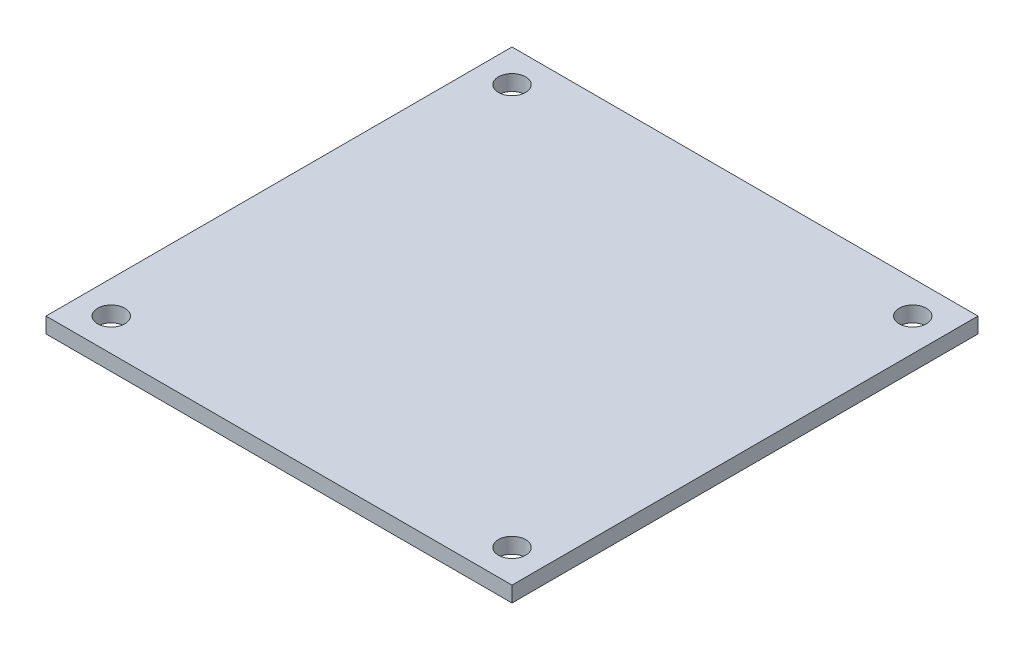
SolidWorks part; units mm, degrees
ref_plane "前视基准面" through (0, 0, 0) normal (0, 0, 1) x (1, 0, 0)
ref_plane "上视基准面" through (0, 0, 0) normal (0, 1, 0) x (1, 0, 0)
ref_plane "右视基准面" through (0, 0, 0) normal (1, 0, 0) x (0, 0, -1)
sketch "草图1" plane through (0, 0, 0) normal (0, 1, 0) x (1, 0, 0)
  line L1 (-30, -30) -> (30, -30)
  line L2 (-30, -30) -> (-30, 30)
  line L3 (-30, 30) -> (30, 30)
  line L4 (30, -30) -> (30, 30)
  line L5 (-30, -30) -> (30, 30) construction
  line L6 (-30, 30) -> (30, -30) construction
  point P0 (0, 0)
  dimension "D1" = 60
  dimension "D2" = 60
extrude "凸台-拉伸1" add sketch "草图1" along normal blind 2
sketch "草图2" plane through (0, 0, 0) normal (0, -1, 0) x (1, 0, 0)
  line L0 (-33.1976, 0) -> (33.3576, 0) construction
  line L1 (0, 32.0617) -> (0, -34.3655) construction
  circle A0 centre (-25.8, 25.8) radius 1.75
  circle A1 centre (25.8, 25.8) radius 1.75
  circle A2 centre (25.8, -25.8) radius 1.75
  circle A3 centre (-25.8, -25.8) radius 1.75
  dimension "D1" = 51.6
  dimension "D2" = 51.6
extrude "切除-拉伸1" cut sketch "草图2" against normal blind 2
